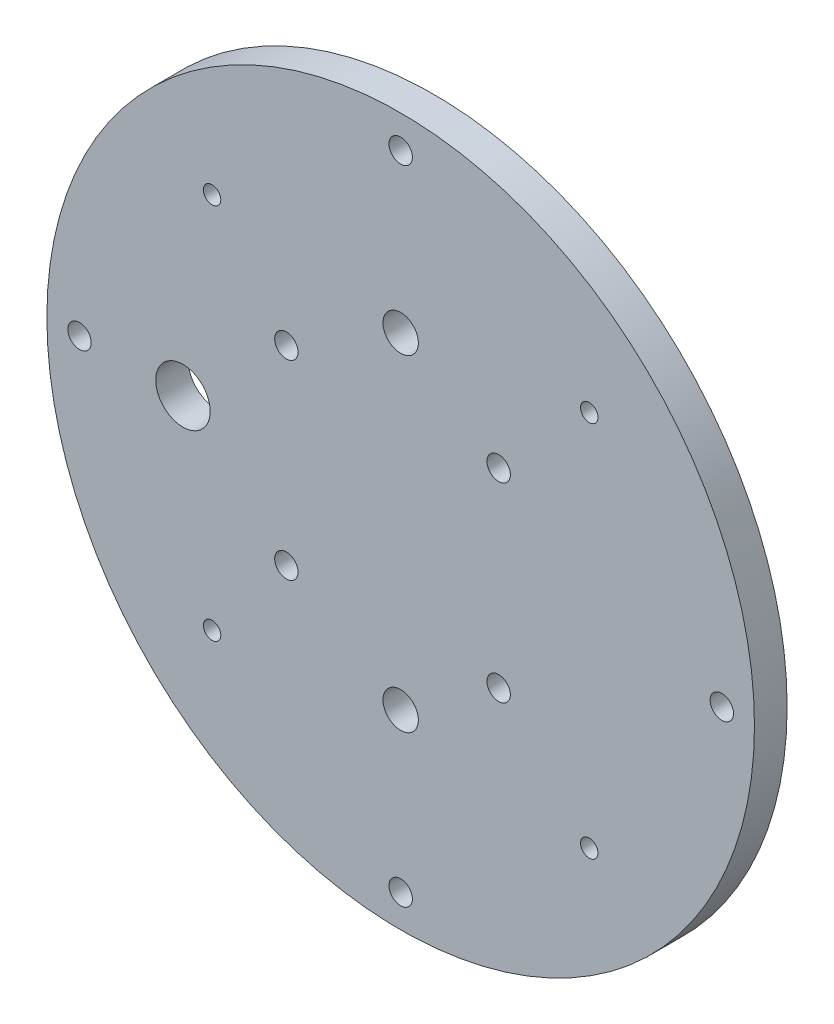
SolidWorks part; units mm, degrees
ref_plane "Front Plane" through (0, 0, 0) normal (0, 0, 1) x (1, 0, 0)
ref_plane "Top Plane" through (0, 0, 0) normal (0, 1, 0) x (1, 0, 0)
ref_plane "Right Plane" through (0, 0, 0) normal (1, 0, 0) x (0, 0, -1)
sketch "草圖1" plane through (0, 0, 0) normal (0, 0, 1) x (1, 0, 0)
  circle A0 centre (0, 0) radius 65
  circle A1 centre (34.6482, 34.6482) radius 1.6
  circle A2 centre (-34.6482, 34.6482) radius 1.6
  circle A3 centre (-34.6482, -34.6482) radius 1.6
  circle A4 centre (34.6482, -34.6482) radius 1.6
  circle A5 centre (59, 0) radius 2.15
  circle A6 centre (0, 59) radius 2.15
  circle A7 centre (-59, 0) radius 2.15
  circle A8 centre (0, -59) radius 2.15
  circle A9 centre (-21, 17.5) radius 2.15
  circle A10 centre (-21, -17.5) radius 2.15
  circle A11 centre (18, 17.5) radius 2.15
  circle A12 centre (18, -17.5) radius 2.15
  circle A13 centre (0, 30) radius 3.25
  circle A14 centre (0, -30) radius 3.25
  circle A15 centre (-40, 0) radius 5
extrude "填料-伸長1" add sketch "草圖1" along normal blind 6
